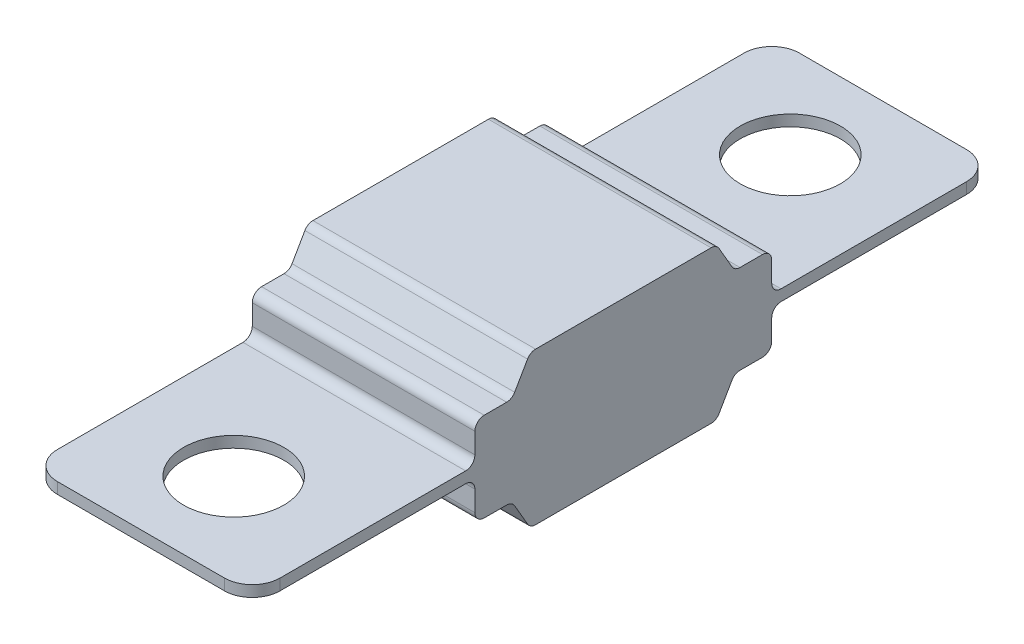
SolidWorks part; units mm, degrees
ref_plane "Ön Düzlem" through (0, 0, 0) normal (0, 0, 1) x (1, 0, 0)
ref_plane "Üst Düzlem" through (0, 0, 0) normal (0, 1, 0) x (1, 0, 0)
ref_plane "Sağ Düzlem" through (0, 0, 0) normal (1, 0, 0) x (0, 0, -1)
sketch "Çizim1" plane through (0, 0, 0) normal (1, 0, 0) x (0, 0, -1)
  line L0 (0, 0.3) -> (61.126, 0.3) construction
  line L1 (0, 0) -> (40, 0)
  line L2 (0, 0) -> (0, 0.6)
  line L3 (0, 0.6) -> (40, 0.6)
  line L4 (40, 0) -> (40, 0.6)
  line L5 (12, 0.6) -> (12, 2.7)
  line L6 (12, 2.7) -> (14, 2.7)
  line L7 (14, 2.7) -> (14.9815, 4.4)
  line L8 (14.9815, 4.4) -> (25.0185, 4.4)
  line L9 (20, 0.6) -> (20, 12.7061) construction
  line L10 (28, 0.6) -> (28, 2.7)
  line L11 (26, 2.7) -> (25.0185, 4.4)
  line L12 (28, 2.7) -> (26, 2.7)
  line L13 (28, -2.1) -> (26, -2.1)
  line L14 (28, 0) -> (28, -2.1)
  line L15 (26, -2.1) -> (25.0185, -3.8)
  line L16 (14.9815, -3.8) -> (25.0185, -3.8)
  line L17 (14, -2.1) -> (14.9815, -3.8)
  line L18 (12, -2.1) -> (14, -2.1)
  line L19 (12, 0) -> (12, -2.1)
  point P14 (0, 0)
  point P18 (20, 4.4)
  dimension "D1" = 40
  dimension "D2" = 0.6
  dimension "D3" = 4.1
  dimension "D4" = 8
  dimension "D5" = 2
  dimension "D6" = 120
  dimension "D7" = 2.1
extrude "Yükseklik-Ekstrüzyon1" add sketch "Çizim1" along normal blind 12 contours L1 L19 L18 L17 L16 L15 L13 L14 | L10 L12 L11 L8 L7 L6 L5 L3 | L1 L4 L3 L2
sketch "Çizim2" plane through (0, 0.6, 0) normal (0, 1, 0) x (1, 0, 0)
  line L0 (12, 40) -> (0, 40) construction
  circle A0 centre (6, 5) radius 2.7
  circle A1 centre (6, 35) radius 2.7
  point P4 (6.1343, 35.6453)
  point P7 (6, 40)
  dimension "D1" = 5.4
  dimension "D2" = 30
  dimension "D3" = 5
extrude "Kes-Ekstrüzyon1" cut sketch "Çizim2" against normal through all
fillet "Radyus1" radius 1.5 4 edges at (0, 0.3, 0) (12, 0.3, 0) (0, 0.3, -40) (12, 0.3, -40)
fillet "Radyus2" radius 0.5 16 edges at (6, 0, -28) (6, -2.1, -28) (6, -2.1, -26) (6, -3.8, -25.0185) (6, -3.8, -14.9815) (6, -2.1, -14) (6, -2.1, -12) (6, 0, -12) (6, 0.6, -28) (6, 2.7, -28) (6, 2.7, -26) (6, 4.4, -25.0185) (6, 0.6, -12) (6, 2.7, -12) (6, 2.7, -14) (6, 4.4, -14.9815)
